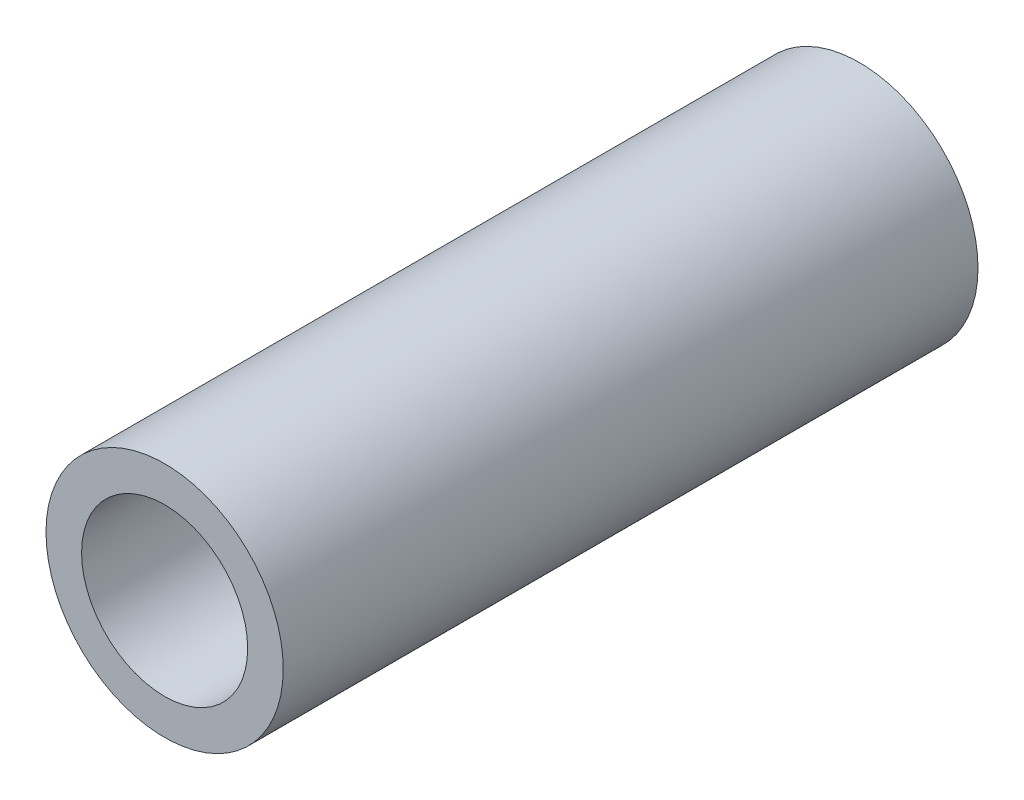
SolidWorks part; units mm, degrees
ref_plane "Front Plane" through (0, 0, 0) normal (0, 0, 1) x (1, 0, 0)
ref_plane "Top Plane" through (0, 0, 0) normal (0, 1, 0) x (1, 0, 0)
ref_plane "Right Plane" through (0, 0, 0) normal (1, 0, 0) x (0, 0, -1)
sketch "Sketch1" plane through (0, 0, 0) normal (0, 0, 1) x (1, 0, 0)
  circle A0 centre (0, 0) radius 1.225
  circle A1 centre (0, 0) radius 1.75
  dimension "D1" = 3.5
  dimension "D2" = 2.45
extrude "Boss-Extrude1" add sketch "Sketch1" along normal blind 10.25
